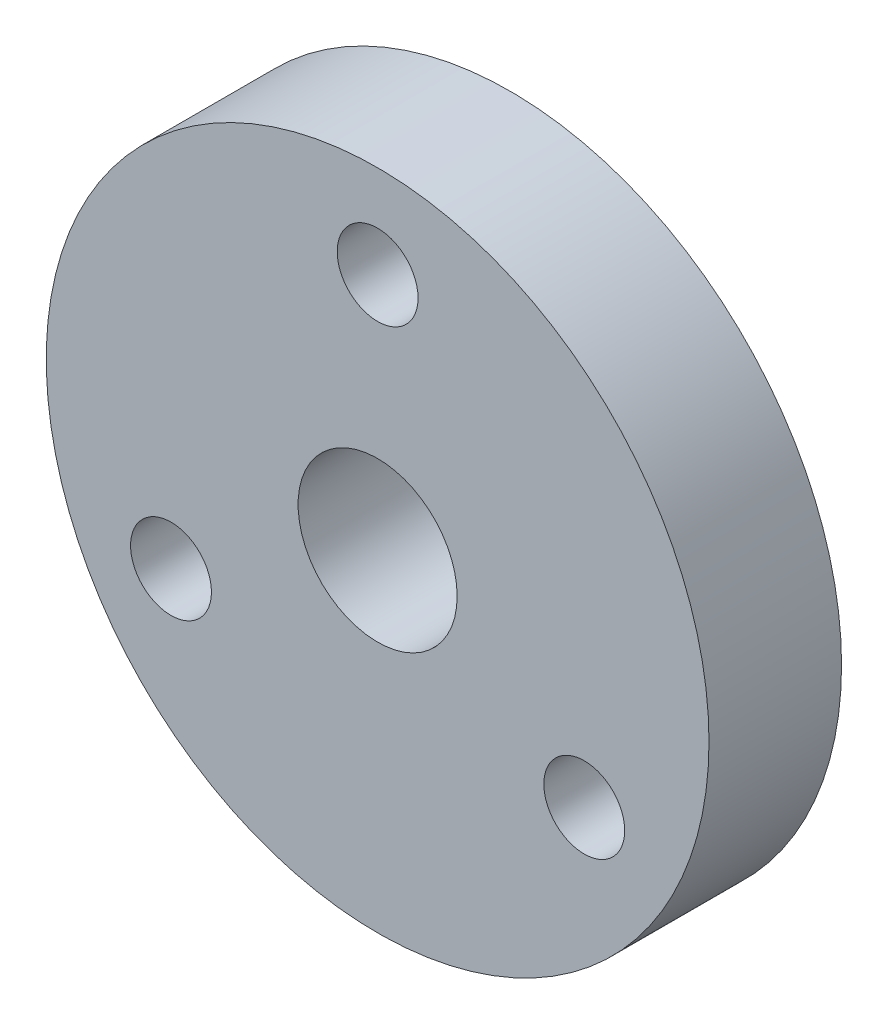
SolidWorks part; units mm, degrees
ref_plane "Front Plane" through (0, 0, 0) normal (0, 0, 1) x (1, 0, 0)
ref_plane "Top Plane" through (0, 0, 0) normal (0, 1, 0) x (1, 0, 0)
ref_plane "Right Plane" through (0, 0, 0) normal (1, 0, 0) x (0, 0, -1)
sketch "Sketch1" plane through (0, 0, 0) normal (0, 0, 1) x (1, 0, 0)
  circle A0 centre (0, 0) radius 12.5
  dimension "D1" = 25
extrude "Boss-Extrude1" add sketch "Sketch1" along normal blind 5
sketch "Sketch3" plane through (0, 0, 5) normal (0, 0, 1) x (1, 0, 0)
  circle A0 centre (0, 0) radius 3
  dimension "D1" = 6
extrude "Cut-Extrude2" cut sketch "Sketch3" against normal up to next
sketch "Sketch4" plane through (0, 0, 5) normal (0, 0, 1) x (1, 0, 0)
  circle A1 centre (0, 9) radius 1.525
  circle A2 centre (7.7942, -4.5) radius 1.525
  circle A3 centre (-7.7942, -4.5) radius 1.525
  point P12 (0, 0)
  dimension "D2" = 3.05
  dimension "D3" = 3
extrude "Cut-Extrude3" cut sketch "Sketch4" against normal up to next
